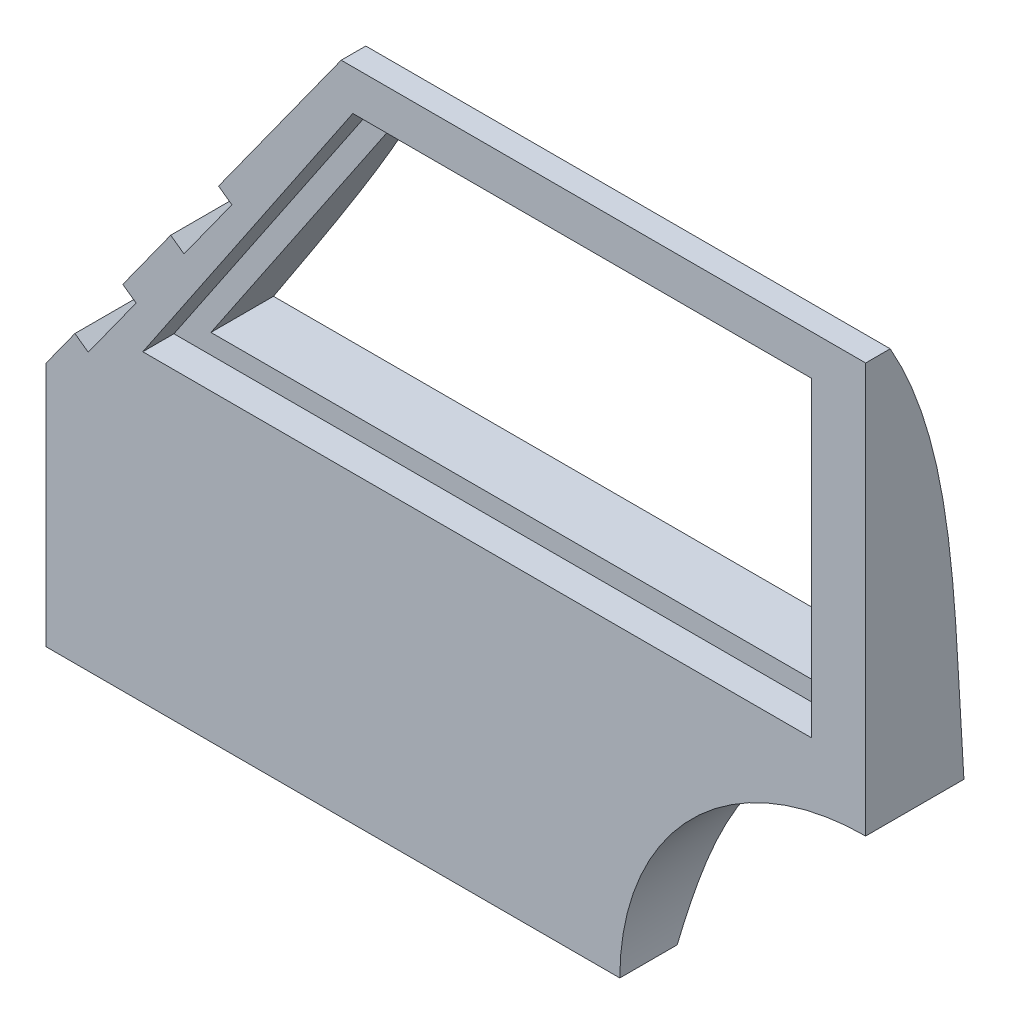
SolidWorks part; units mm, degrees
material "7075-T6, Plate (SS)"
ref_plane "Front Plane" through (0, 0, 0) normal (0, 0, 1) x (1, 0, 0)
ref_plane "Top Plane" through (0, 0, 0) normal (0, 1, 0) x (1, 0, 0)
ref_plane "Right Plane" through (0, 0, 0) normal (1, 0, 0) x (0, 0, -1)
sketch "Sketch1" plane through (0, 0, 0) normal (0, 0, 1) x (1, 0, 0)
  line L0 (0, 0) -> (0, 381)
  line L1 (0, 381) -> (457.2, 1016)
  line L2 (457.2, 1016) -> (1270, 1016)
  line L3 (1270, 1016) -> (1270, 381)
  line L4 (889, 0) -> (0, 0)
  arc A0 (1270, 381) -> (889, 0) centre (1270, 0) ccw
  dimension "D5" = 762
  dimension "D7" = 381
  dimension "D1" = 812.8
  dimension "D2" = 1016
  dimension "D3" = 381
  dimension "D4" = 1270
  dimension "D6" = 635
  dimension "D8" = 889
extrude "Boss-Extrude1" add sketch "Sketch1" along normal blind 152.4
sketch "Sketch3" plane through (1270, 0, 0) normal (1, 0, 0) x (0, 0, -1)
  line L0 (0, 1016) -> (-114.3, 1016)
  line L1 (-152.4, 1016) -> (0, 1016) construction
  line L2 (0, 1016) -> (0, 381)
  line L3 (0, 381) -> (0, 1016) construction
  line L4 (-152.4, 381) -> (0, 381) construction
  spline S0 degree 3 poles (-114.3, 1016) (-8.4092, 829.104) (-15.8704, 600.1288) (0, 381) knots 0 0 0 0 1 1 1 1
  dimension "D1" = 114.3
sketch "Sketch4" plane through (0, 0, 0) normal (-1, 0, 0) x (0, 0, 1)
  line L0 (0, 0) -> (63.5, 0)
  line L1 (152.4, 0) -> (0, 0) construction
  line L2 (0, 381) -> (0, 0)
  spline S0 degree 3 poles (0, 381) (19.9482, 253.8029) (11.0592, 124.8188) (63.5, 0) knots 0 0 0 0 1 1 1 1
  dimension "D1" = 63.5
extrude "Cut-Extrude1" cut sketch "Sketch3" against normal through all and the other way through all
extrude "Cut-Extrude2" cut sketch "Sketch4" against normal through all
fillet "Fillet1" radius 50.8 1 edges at (635, 381, 0)
sketch "Sketch5" plane through (0, 0, 152.4) normal (0, 0, 1) x (1, 0, 0)
  line L0 (1186.4045, 953.508) -> (1186.4045, 470.908)
  line L1 (1186.4045, 470.908) -> (149.6867, 470.908)
  line L2 (149.6867, 470.908) -> (475.2045, 953.508)
  line L3 (475.2045, 953.508) -> (1186.4045, 953.508)
  line L4 (1270, 381) -> (1270, 1016) construction
  line L5 (0, 0) -> (889, 0) construction
  dimension "D1" = 482.6
  dimension "D2" = 711.2
  dimension "D3" = 56
  dimension "D4" = 1036.7178
  dimension "D5" = 83.5955
  dimension "D6" = 470.908
extrude "Cut-Extrude3" cut sketch "Sketch5" against normal blind 48.26
sketch3d "3DSketch1"
  line L0 (491.411, 923.028, 104.14) -> (207.0113, 501.388, 104.14)
  line L1 (207.0113, 501.388, 104.14) -> (1155.9245, 501.388, 104.14)
  line L2 (1155.9245, 501.388, 104.14) -> (1155.9245, 923.028, 104.14)
  line L3 (1155.9245, 923.028, 104.14) -> (491.411, 923.028, 104.14)
  line L4 (491.411, 923.028, 104.14) -> (207.0113, 501.388, 104.14)
  line L5 (207.0113, 501.388, 104.14) -> (1155.9245, 501.388, 104.14)
  line L6 (1155.9245, 501.388, 104.14) -> (1155.9245, 923.028, 104.14)
  line L7 (1155.9245, 923.028, 104.14) -> (491.411, 923.028, 104.14)
  dimension "D1" = 30.48
extrude "Cut-Extrude4" cut sketch "3DSketch1" along direction (0, 0, -1) on the side of the normal through all
sketch "Sketch6" plane through (-180.6639, 130.078, 0) normal (-0.8115, 0.5843, 0) x (0, 0, 1)
  line L0 (152.4, 1091.663) -> (152.4, 309.1946) construction
  line L1 (152.4, 385.3946) -> (50.8, 385.3946)
  line L2 (152.4, 385.3946) -> (152.4, 512.3946)
  line L3 (152.4, 512.3946) -> (50.8, 512.3946)
  line L4 (50.8, 385.3946) -> (50.8, 512.3946)
  dimension "D1" = 76.2
  dimension "D2" = 101.6
  dimension "D3" = 127
extrude "Cut-Extrude5" cut sketch "Sketch6" against normal blind 25.4
pattern_linear "LPattern1" count 2 spacing 254 along (0.5843, 0.8115, 0) of "Cut-Extrude5"
ref_plane "Plane1" through (0, 0, -16.1722) normal (0, 0, 1) x (1, 0, 0)
sketch "Sketch7" plane through (0, 0, -16.1722) normal (0, 0, 1) x (1, 0, 0)
  line L1 (952.5, 422.9312) -> (647.7, 422.9312)
  line L2 (952.5, 422.9312) -> (952.5, 295.9312)
  line L3 (952.5, 295.9312) -> (647.7, 295.9312)
  line L4 (647.7, 422.9312) -> (647.7, 295.9312)
  line L5 (952.5, 422.9312) -> (647.7, 295.9312) construction
  line L6 (952.5, 295.9312) -> (647.7, 422.9312) construction
  point P0 (800.1, 359.4312)
  dimension "D1" = 304.8
  dimension "D2" = 127
  dimension "D3" = 647.7
  dimension "D4" = 295.9312
extrude "Cut-Extrude7" cut sketch "Sketch7" along normal blind 114.3
